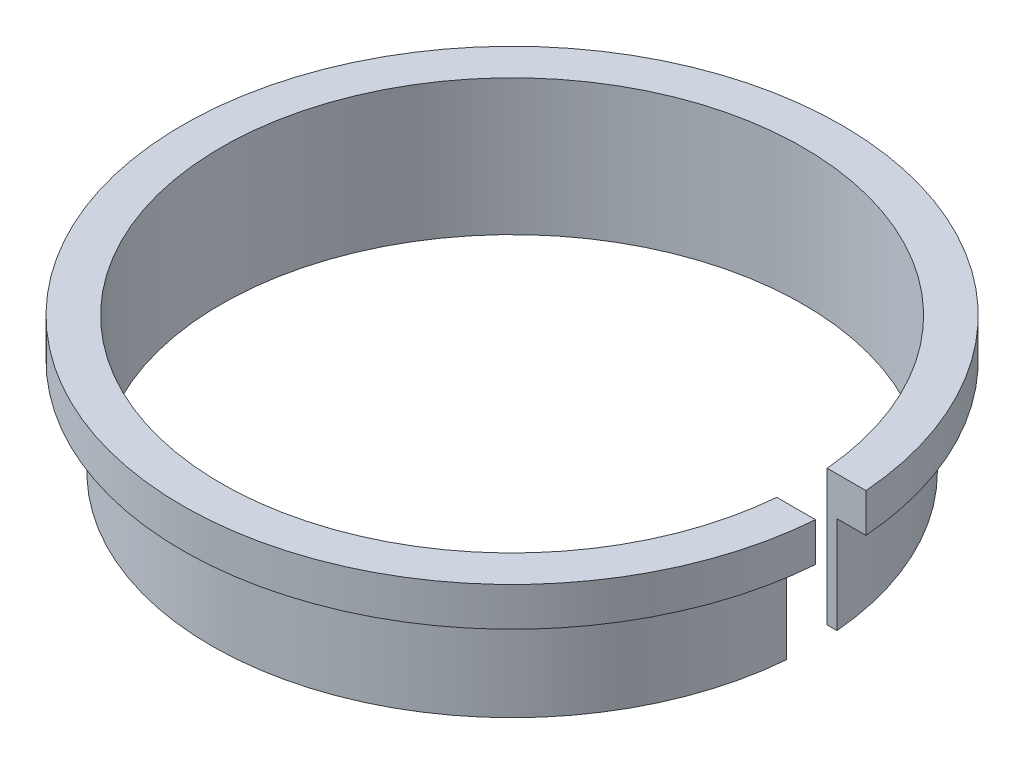
SolidWorks part; units mm, degrees
ref_plane "Front Plane" through (0, 0, 0) normal (0, 0, 1) x (1, 0, 0)
ref_plane "Top Plane" through (0, 0, 0) normal (0, 1, 0) x (1, 0, 0)
ref_plane "Right Plane" through (0, 0, 0) normal (1, 0, 0) x (0, 0, -1)
sketch "Sketch1" plane through (0, 0, 0) normal (0, 1, 0) x (1, 0, 0)
  circle A0 centre (0, 0) radius 15
  circle A1 centre (0, 0) radius 15.5
  dimension "D1" = 30
  dimension "D2" = 31
extrude "Boss-Extrude1" add sketch "Sketch1" along normal blind 7
sketch "Sketch2" plane through (0, 7, 0) normal (0, 1, 0) x (1, 0, 0)
  circle A0 centre (0, 0) radius 16.99
  circle A1 centre (0, 0) radius 15.5 construction
  circle A2 centre (0, 0) radius 15.5
  dimension "D1" = 33.98
extrude "Boss-Extrude2" add sketch "Sketch2" against normal blind 2
ref_plane "Plane1" through (16.99, 0, 0) normal (1, 0, 0) x (0, 0, -1)
sketch "Sketch3" plane through (16.99, 0, 0) normal (1, 0, 0) x (0, 0, -1)
  line L0 (-15.5, 0) -> (15.5, 0) construction
  line L1 (-1.2991, 7) -> (1.2991, 7)
  line L2 (-1.2991, 7) -> (-1.2991, 0)
  line L3 (-1.2991, 0) -> (1.2991, 0)
  line L4 (1.2991, 7) -> (1.2991, 0)
  line L5 (-1.2991, 7) -> (1.2991, 0) construction
  line L6 (-1.2991, 0) -> (1.2991, 7) construction
  line L7 (16.99, 7) -> (-16.99, 7) construction
  point P0 (0, 3.5)
  dimension "D1" = 1.2991
extrude "Cut-Extrude1" cut sketch "Sketch3" against normal blind 10
